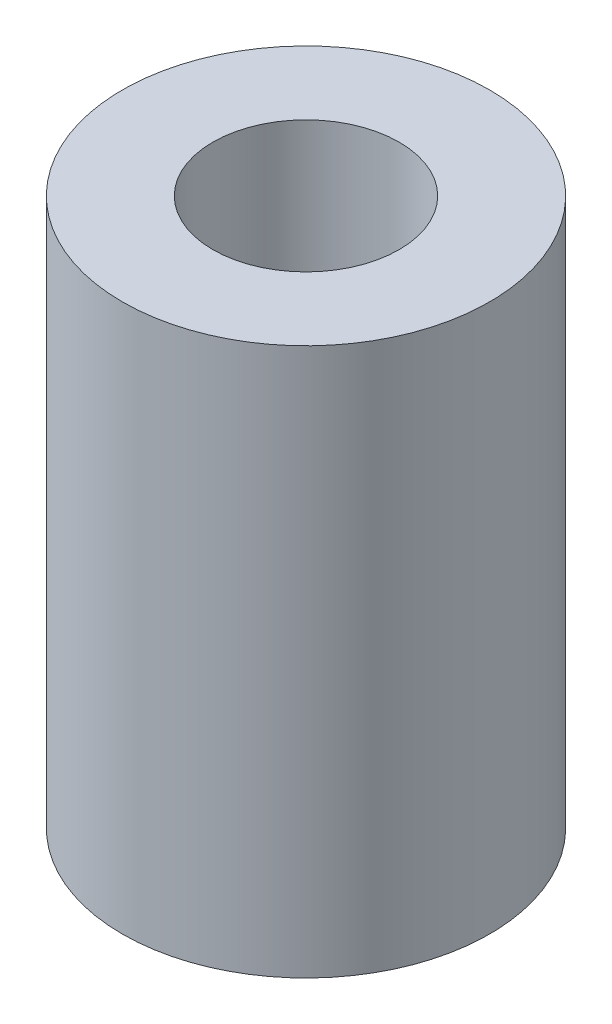
SolidWorks part; units mm, degrees
material "KNSB"
ref_plane "Plano frontal" through (0, 0, 0) normal (0, 0, 1) x (1, 0, 0)
ref_plane "Plano superior" through (0, 0, 0) normal (0, 1, 0) x (1, 0, 0)
ref_plane "Plano direito" through (0, 0, 0) normal (1, 0, 0) x (0, 0, -1)
sketch "Esboço1" plane through (0, 0, 0) normal (0, 1, 0) x (1, 0, 0)
  circle A0 centre (0, 0) radius 18.32
  circle A1 centre (0, 0) radius 9.295
  point P34 (0, 0)
  dimension "D4" = 36.64
  dimension "D1" = 18.59
extrude "Ressalto-extrusão1" add sketch "Esboço1" along normal blind 54.63
